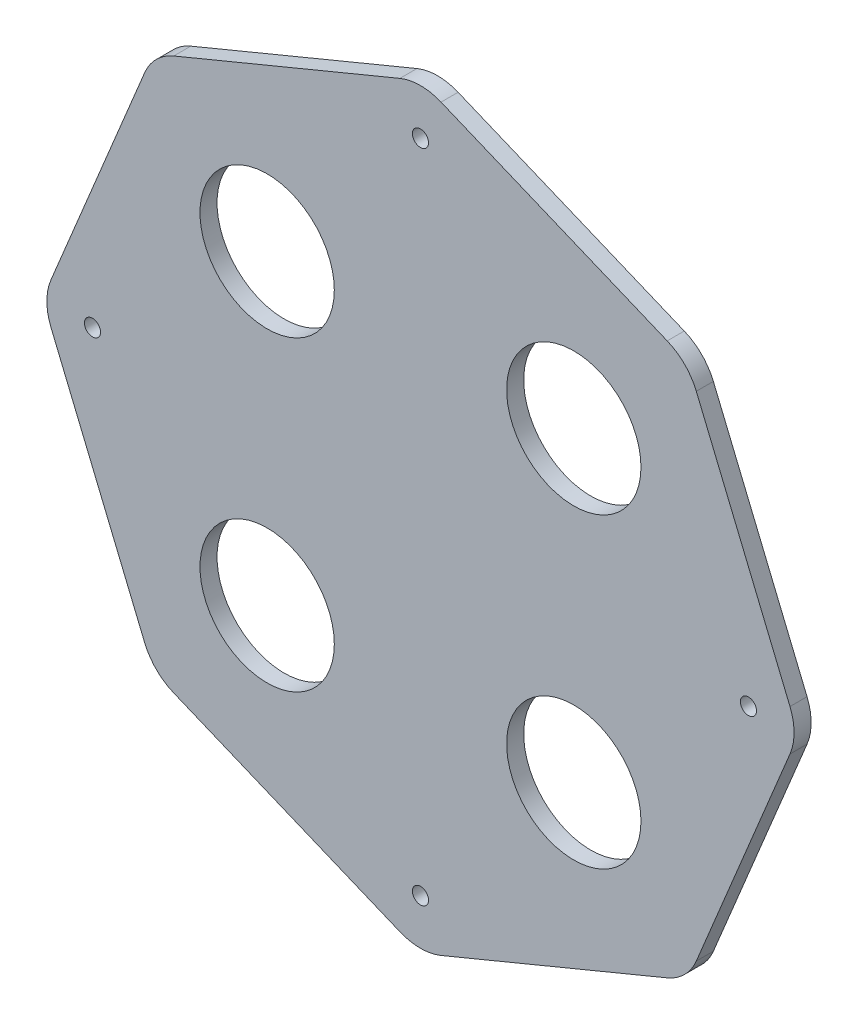
SolidWorks part; units mm, degrees
ref_plane "Front Plane" through (0, 0, 0) normal (0, 0, 1) x (1, 0, 0)
ref_plane "Top Plane" through (0, 0, 0) normal (0, 1, 0) x (1, 0, 0)
ref_plane "Right Plane" through (0, 0, 0) normal (1, 0, 0) x (0, 0, -1)
sketch "Sketch1" plane through (0, 0, 0) normal (0, 0, 1) x (1, 0, 0)
  line L1 (70.3555, 0) -> (49.7488, 49.7488)
  line L2 (49.7488, 49.7488) -> (0, 70.3555)
  line L3 (0, 70.3555) -> (-49.7488, 49.7488)
  line L4 (-49.7488, 49.7488) -> (-70.3555, 0)
  line L5 (-70.3555, 0) -> (-49.7488, -49.7488)
  line L6 (-49.7488, -49.7488) -> (0, -70.3555)
  line L7 (0, -70.3555) -> (49.7488, -49.7488)
  line L8 (49.7488, -49.7488) -> (70.3555, 0)
  line L11 (49.7488, 49.7488) -> (28.5356, 28.5356) construction
  line L12 (-49.7488, -49.7488) -> (-28.5356, -28.5356) construction
  line L13 (49.7488, -49.7488) -> (28.5356, -28.5356) construction
  circle A0 centre (0, 0) radius 65 construction
  circle A1 centre (0, 61.04) radius 1.5
  circle A2 centre (61.04, 0) radius 1.5
  circle A3 centre (0, -61.04) radius 1.5
  circle A4 centre (-61.04, 0) radius 1.5
  circle A5 centre (-28.5356, 28.5356) radius 12.5
  circle A6 centre (28.5356, 28.5356) radius 12.5
  circle A7 centre (-28.5356, -28.5356) radius 12.5
  circle A8 centre (28.5356, -28.5356) radius 12.5
  dimension "D1" = 130
  dimension "D4" = 3
  dimension "D5" = 3
  dimension "D6" = 3
  dimension "D7" = 3
  dimension "D12" = 25
  dimension "D13" = 25
  dimension "D15" = 25
  dimension "D8" = 30
  dimension "D10" = 30
  dimension "D11" = 30
extrude "Boss-Extrude1" add sketch "Sketch1" along normal blind 3.175
fillet "Fillet1" radius 10 7 edges at (-70.3555, 0, 1.5875) (-49.7488, -49.7488, 1.5875) (0, -70.3555, 1.5875) (49.7488, -49.7488, 1.5875) (70.3555, 0, 1.5875) (49.7488, 49.7488, 1.5875) (0, 70.3555, 1.5875)
fillet "Fillet2" radius 10 1 edges at (-49.7488, 49.7488, 1.5875)
